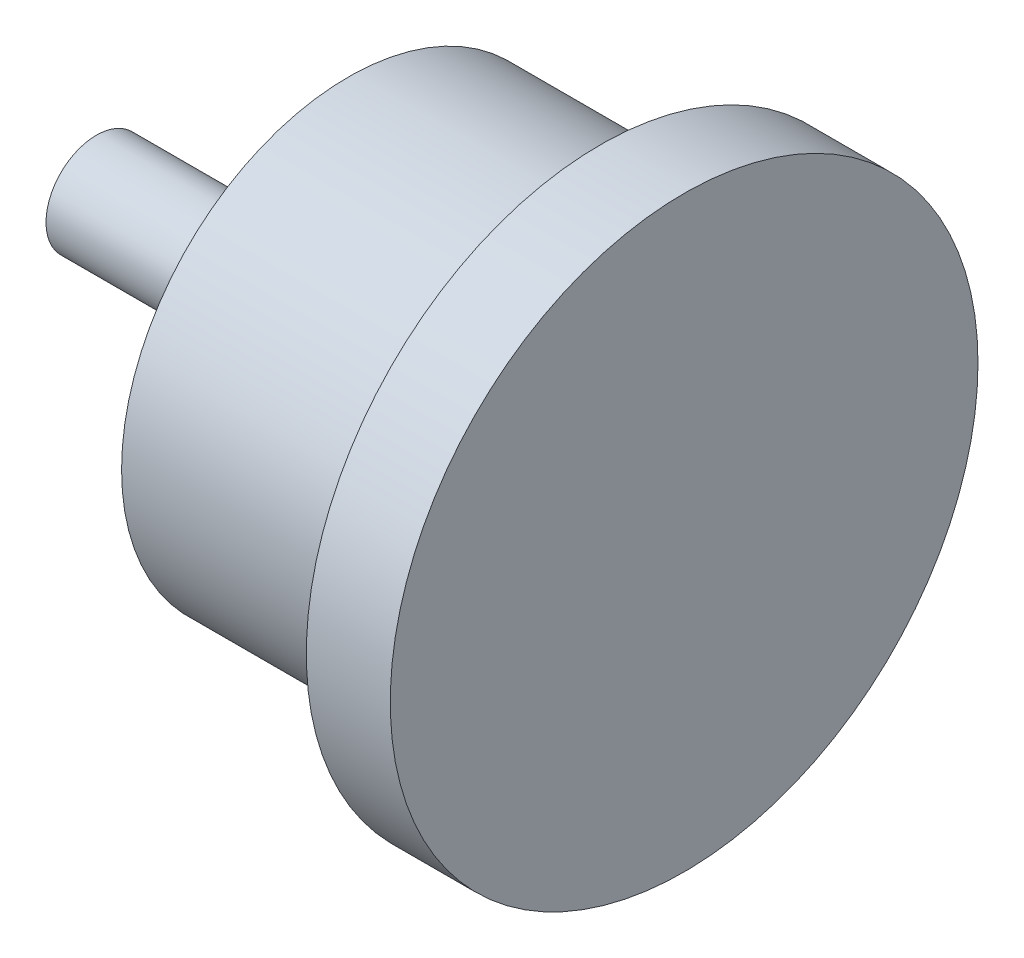
SolidWorks part; units mm, degrees
ref_plane "Front Plane" through (0, 0, 0) normal (0, 0, 1) x (1, 0, 0)
ref_plane "Top Plane" through (0, 0, 0) normal (0, 1, 0) x (1, 0, 0)
ref_plane "Right Plane" through (0, 0, 0) normal (1, 0, 0) x (0, 0, -1)
sketch "Sketch1" plane through (0, 0, 0) normal (1, 0, 0) x (0, 0, -1)
  circle A0 centre (0, 0) radius 17.5
  dimension "D1" = 35
extrude "Boss-Extrude1" add sketch "Sketch1" along normal blind 5
sketch "Sketch2" plane through (0, 0, 0) normal (-1, 0, 0) x (0, 0, 1)
  circle A0 centre (0, 0) radius 13.5
  dimension "D1" = 27
extrude "Boss-Extrude2" add sketch "Sketch2" along normal blind 15
sketch "Sketch3" plane through (-15, 0, 0) normal (-1, 0, 0) x (0, 0, 1)
  circle A0 centre (0, 0) radius 3
  dimension "D1" = 6
extrude "Boss-Extrude3" add sketch "Sketch3" along normal blind 15
